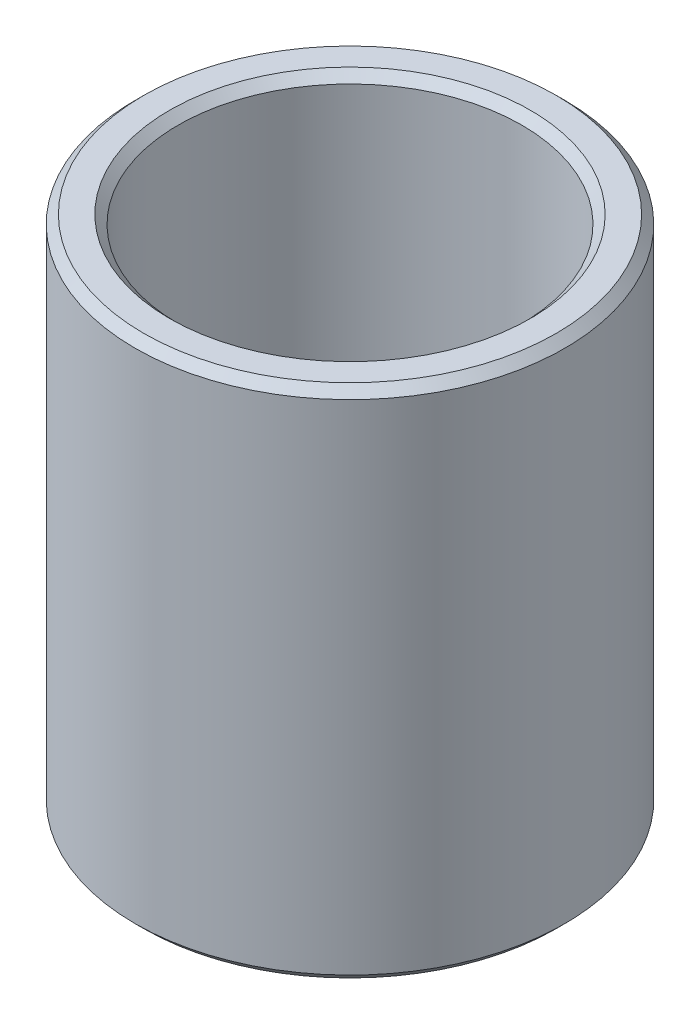
SolidWorks part; units mm, degrees
ref_plane "Face" through (0, 0, 0) normal (0, 0, 1) x (1, 0, 0)
ref_plane "Dessus" through (0, 0, 0) normal (0, 1, 0) x (1, 0, 0)
ref_plane "Droite" through (0, 0, 0) normal (1, 0, 0) x (0, 0, -1)
sketch "Esquisse1" plane through (0, 0, 0) normal (0, 0, 1) x (1, 0, 0)
  line L0 (0, 0) -> (0, 40) construction
  line L1 (4, 12) -> (5, 12)
  line L2 (5, 12) -> (5, 0)
  line L3 (5, 0) -> (4, 0)
  line L4 (4, 0) -> (4, 12)
  dimension "D1" = 8
  dimension "D2" = 10
  dimension "D3" = 12
revolve "Base-Révolution" add sketch "Esquisse1" angle 360 about L0
chamfer "Chanfrein1" distance 0.2 angle 45
